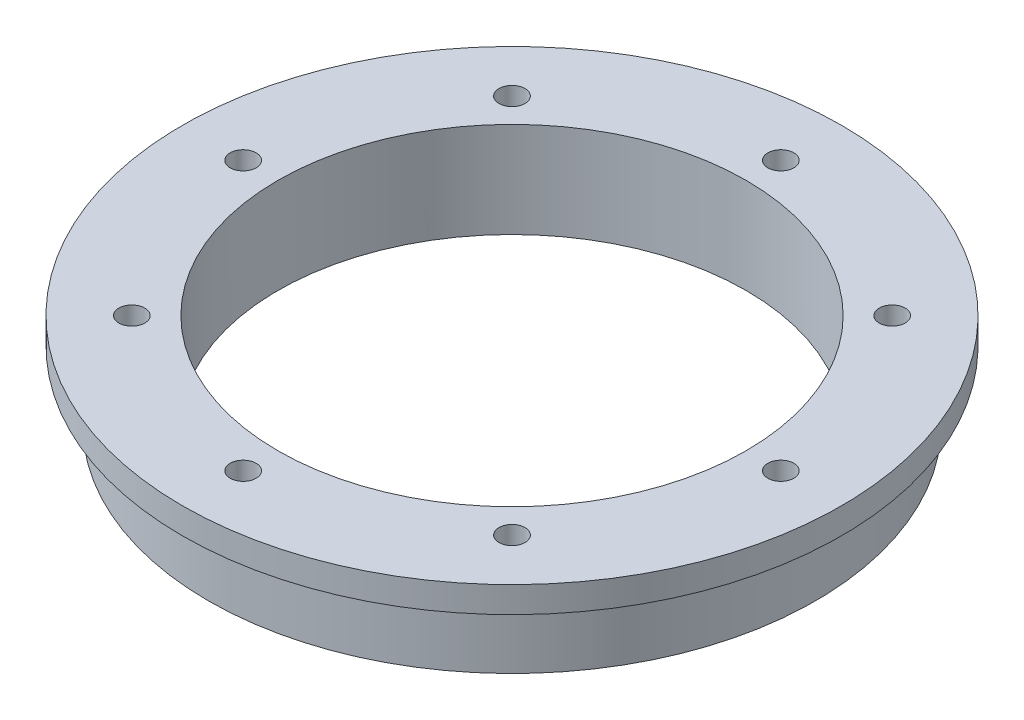
SolidWorks part; units mm, degrees
material "6061 合金"
ref_plane "前视基准面" through (0, 0, 0) normal (0, 0, 1) x (1, 0, 0)
ref_plane "上视基准面" through (0, 0, 0) normal (0, 1, 0) x (1, 0, 0)
ref_plane "右视基准面" through (0, 0, 0) normal (1, 0, 0) x (0, 0, -1)
other "Configuration Table"
sketch "草图1" plane through (0, 0, 0) normal (0, 1, 0) x (1, 0, 0)
  line L0 (35, 0) -> (38, 0) construction
  line L1 (0, 35) -> (0, 27) construction
  circle A0 centre (0, 0) radius 38
  circle A1 centre (0, 0) radius 35 construction
  circle A2 centre (0, 0) radius 27
  point P31 (0, 0)
  dimension "D1" = 70
  dimension "D2" = 3
  dimension "D3" = 8
extrude "凸台-拉伸1" add sketch "草图1" along normal blind 3
sketch "草图2" plane through (0, 0, 0) normal (0, -1, 0) x (1, 0, 0)
  circle A0 centre (0, 0) radius 35
  circle A1 centre (0, 0) radius 27
  circle A2 centre (0, 0) radius 27 construction
  point P21 (0, 0)
  dimension "D1" = 70
extrude "凸台-拉伸2" add sketch "草图2" along normal blind 8
sketch "草图4" plane through (0, -8, 0) normal (0, -1, 0) x (1, 0, 0)
  line L0 (0, 35) -> (0, 27) construction
  circle A0 centre (0, 0) radius 35 construction
  circle A1 centre (0, 0) radius 35 construction
  circle A2 centre (0, 0) radius 27 construction
  circle A3 centre (0, 31) radius 1.5
  circle A4 centre (21.9203, 21.9203) radius 1.5
  circle A5 centre (31, 0) radius 1.5
  circle A6 centre (21.9203, -21.9203) radius 1.5
  circle A7 centre (0, -31) radius 1.5
  circle A8 centre (-21.9203, -21.9203) radius 1.5
  circle A9 centre (-31, 0) radius 1.5
  circle A10 centre (-21.9203, 21.9203) radius 1.5
  point P27 (0, 0)
  dimension "D1" = 3
  dimension "D2" = 8
extrude "切除-拉伸1" cut sketch "草图4" against normal through all
